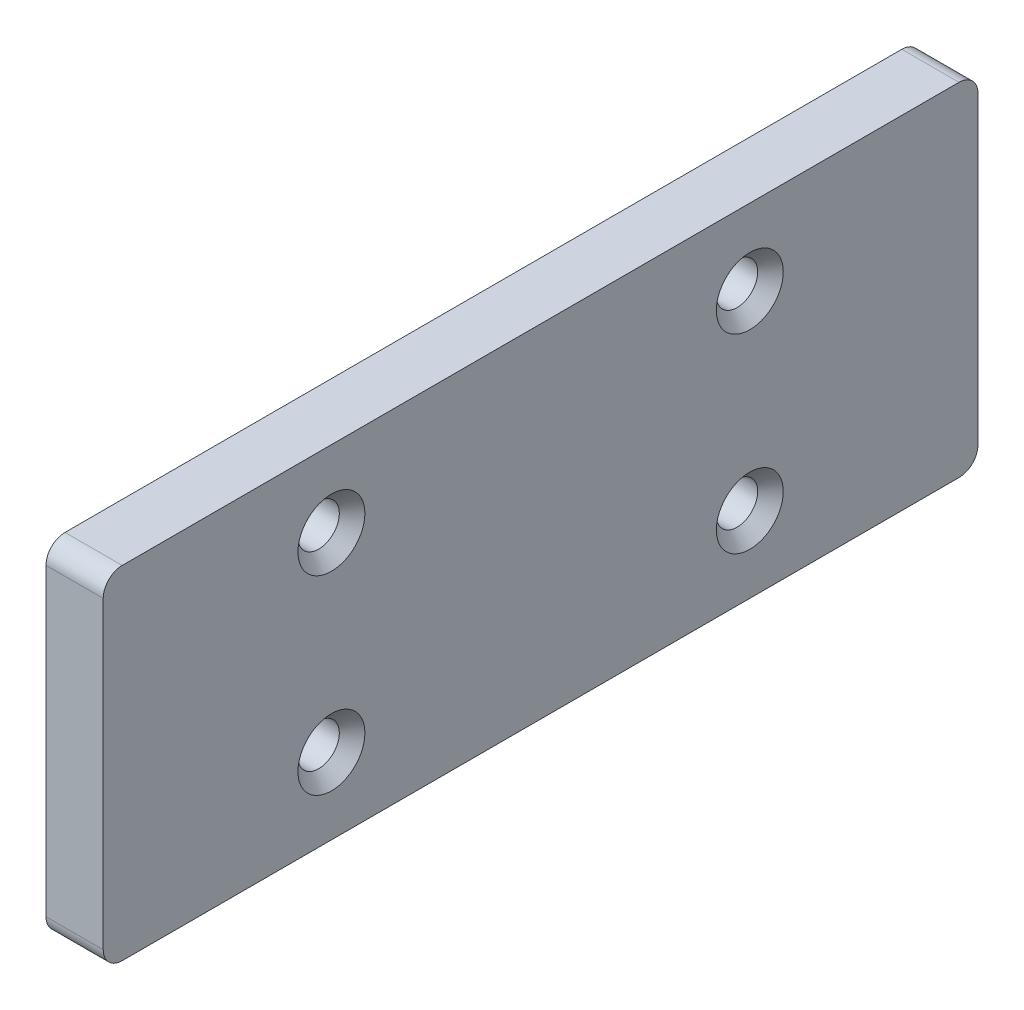
SolidWorks part; units mm, degrees
ref_plane "Front Plane" through (0, 0, 0) normal (0, 0, 1) x (1, 0, 0)
ref_plane "Top Plane" through (0, 0, 0) normal (0, 1, 0) x (1, 0, 0)
ref_plane "Right Plane" through (0, 0, 0) normal (1, 0, 0) x (0, 0, -1)
sketch "Sketch1" plane through (0, 0, 0) normal (1, 0, 0) x (0, 0, -1)
  line L1 (-36.5125, 14.2875) -> (36.5125, 14.2875)
  line L2 (-36.5125, 14.2875) -> (-36.5125, -14.2875)
  line L3 (-36.5125, -14.2875) -> (36.5125, -14.2875)
  line L4 (36.5125, 14.2875) -> (36.5125, -14.2875)
  point P4 (36.5125, 0)
  point P5 (0, 14.2875)
  dimension "D1" = 28.575
  dimension "D2" = 73.025
extrude "Boss-Extrude1" add sketch "Sketch1" against normal blind 4.7752
hole_wizard "#8-32 Tapped Hole1" positions "Sketch3" profile "Sketch2" tap size "#8-32" standard "Ansi Inch" end condition up to next
sketch "Sketch3" plane through (0, 0, 0) normal (1, 0, 0) x (0, 0, -1)
  line L0 (0, 7.248) -> (0, 35.4541) construction
  point P0 (17.4625, -7.9502)
  point P1 (17.4625, 7.9248)
  point P3 (-17.4625, 7.9248)
  point P5 (-17.4625, -7.9502)
  dimension "D1" = 7.9502
  dimension "D2" = 15.875
  dimension "D3" = 34.925
sketch "Sketch2" plane through (0, -7.9502, -17.4625) normal (0, 1, 0) x (0, 0, -1)
  line L0 (0, 0) -> (0, 4.7752)
  line L1 (0, 4.7752) -> (2.286, 4.7752)
  line L2 (1.7272, 4.2164) -> (1.7272, 1.0668)
  line L3 (1.7272, 1.0668) -> (2.794, 0)
  line L5 (2.794, 0) -> (0, 0)
  line L6 (-1.7272, 1.0668) -> (-2.794, 0) construction
  line L7 (2.286, 4.7752) -> (1.7272, 4.2164)
  line L8 (-2.286, 4.7752) -> (-1.7272, 4.2164) construction
  line L11 (0, -6.35) -> (0, 107.95) construction
  dimension "Thru Tap Drill Dia." = 3.4544
  dimension "Thru Tap Drill Depth" = 4.7752
  dimension "Near C'Sink Dia." = 5.588
  dimension "Near C'Sink Angle" = 90
  dimension "Far C'Sink Dia." = 4.572
  dimension "Far C'Sink Angle" = 90
cosmetic thread "Hole Thread2"
cosmetic thread "Hole Thread3"
cosmetic thread "Hole Thread5"
cosmetic thread "Hole Thread6"
fillet "Fillet1" radius 1.5875 4 edges at (-2.3876, 14.2875, -36.5125) (-2.3876, -14.2875, -36.5125) (-2.3876, 14.2875, 36.5125) (-2.3876, -14.2875, 36.5125)
